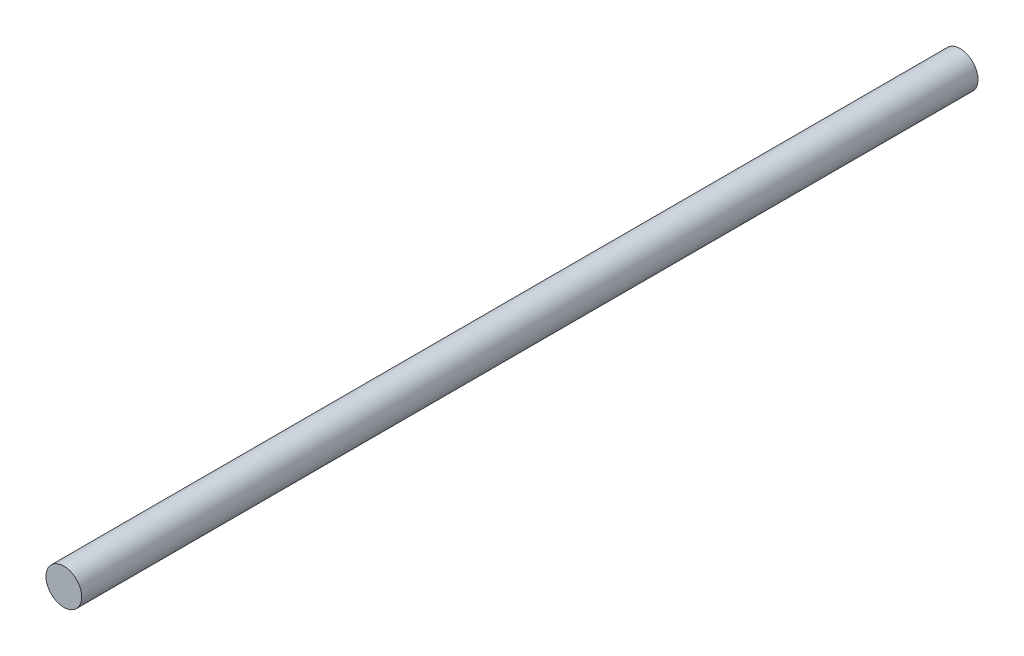
SolidWorks part; units mm, degrees
ref_plane "Front Plane" through (0, 0, 0) normal (0, 0, 1) x (1, 0, 0)
ref_plane "Top Plane" through (0, 0, 0) normal (0, 1, 0) x (1, 0, 0)
ref_plane "Right Plane" through (0, 0, 0) normal (1, 0, 0) x (0, 0, -1)
sketch "草圖1" plane through (0, 0, 0) normal (0, 0, 1) x (1, 0, 0)
  circle A0 centre (0, 0) radius 1.5
extrude "填料-伸長1" add sketch "草圖1" along normal blind 75.24
